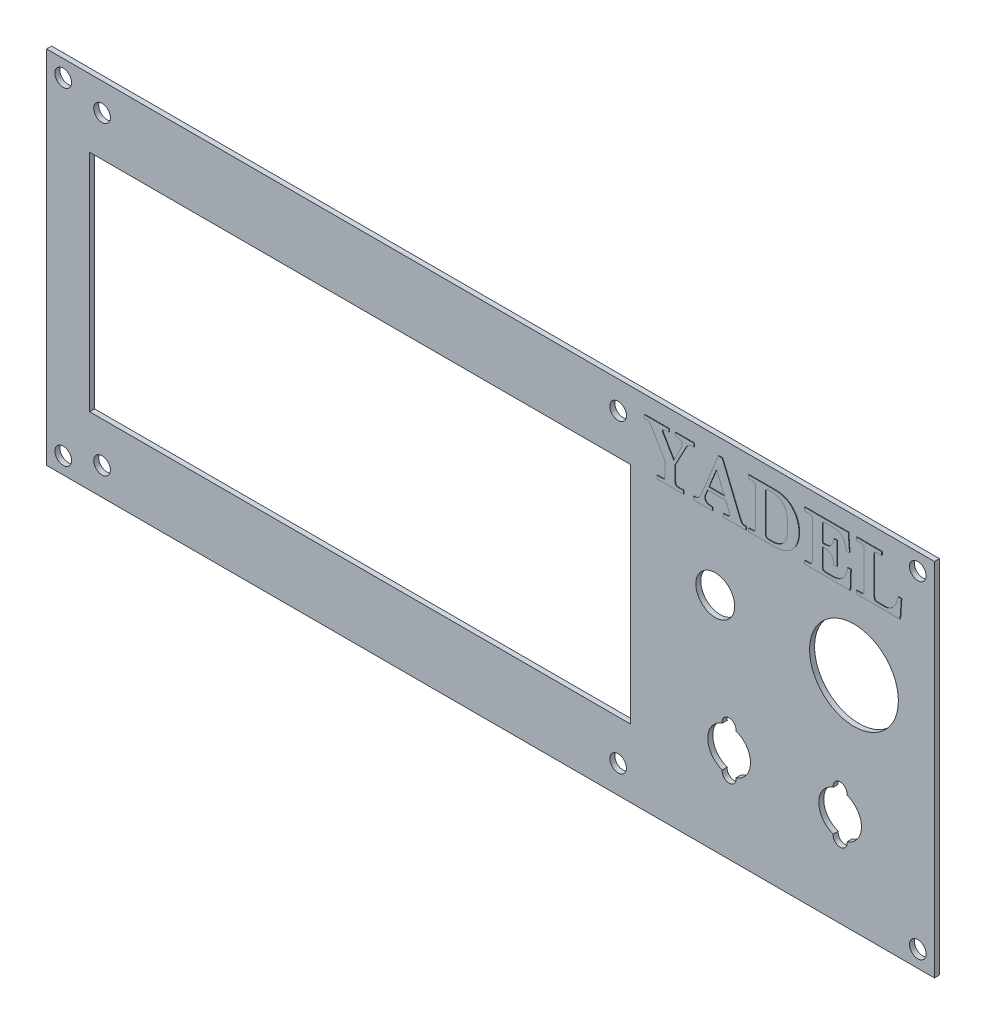
SolidWorks part; units mm, degrees
ref_plane "Plan de face" through (0, 0, 0) normal (0, 0, 1) x (1, 0, 0)
ref_plane "Plan de dessus" through (0, 0, 0) normal (0, 1, 0) x (1, 0, 0)
ref_plane "Plan de droite" through (0, 0, 0) normal (1, 0, 0) x (0, 0, -1)
sketch "Esquisse1" plane through (0, 0, 0) normal (0, 0, 1) x (1, 0, 0)
  line L1 (0, 0) -> (160, 0)
  line L2 (0, 0) -> (0, 65)
  line L3 (0, 65) -> (160, 65)
  line L4 (160, 0) -> (160, 65)
  circle A0 centre (3, 62) radius 1.5
  circle A1 centre (3, 3) radius 1.5
  circle A2 centre (157, 3) radius 1.5
  circle A3 centre (157, 62) radius 1.5
  point P13 (0, 0)
  point P15 (157.8238, 0)
  dimension "D9" = 3
  dimension "D10" = 3
  dimension "D11" = 3
  dimension "D12" = 3
  dimension "D1" = 65
  dimension "D2" = 160
  dimension "D3" = 3
  dimension "D4" = 3
  dimension "D5" = 3
  dimension "D6" = 3
  dimension "D7" = 3
  dimension "D8" = 3
  dimension "D13" = 3
  dimension "D14" = 3
extrude "Boss.-Extru.1" add sketch "Esquisse1" along normal blind 0.9
sketch "Esquisse2" plane through (0, 0, 0.9) normal (0, 0, 1) x (1, 0, 0)
  line L1 (7.75, 52.75) -> (105.25, 52.75)
  line L2 (7.75, 52.75) -> (7.75, 12.25)
  line L3 (7.75, 12.25) -> (105.25, 12.25)
  line L4 (105.25, 52.75) -> (105.25, 12.25)
  line L5 (7.5, 62.5) -> (105.5, 62.5)
  line L6 (7.5, 62.5) -> (7.5, 2.5)
  line L7 (7.5, 2.5) -> (105.5, 2.5)
  line L8 (105.5, 62.5) -> (105.5, 2.5)
  line L9 (0, 65) -> (0, 0) construction
  line L10 (143, 22.1) -> (143, 11.9) construction
  line L11 (123, 11.9) -> (123, 22.1) construction
  line L12 (123, 17) -> (143, 17) construction
  line L14 (145.5, 40) -> (120.5, 40) construction
  line L16 (160, 0) -> (160, 65) construction
  line L17 (160, 65) -> (0, 65) construction
  line L18 (0, 0) -> (160, 0) construction
  circle A0 centre (10, 5) radius 1.5
  circle A1 centre (103, 5) radius 1.5
  circle A2 centre (103, 60) radius 1.5
  circle A3 centre (10, 60) radius 1.5
  circle A4 centre (123, 17) radius 3.85
  circle A5 centre (143, 17) radius 3.85
  circle A6 centre (123, 20.85) radius 1.25
  circle A7 centre (123, 13.15) radius 1.25
  circle A8 centre (143, 20.85) radius 1.25
  circle A9 centre (143, 13.15) radius 1.25
  circle A10 centre (120.5, 40) radius 3.5
  circle A11 centre (145.5, 40) radius 8
  circle A12 centre (120.5, 40) radius 10
  point P18 (0, 32.5)
  point P19 (7.5, 32.5)
  point P20 (7.75, 32.5)
  point P21 (56.5, 62.5)
  point P22 (56.5, 52.75)
  point P42 (133, 40)
  point P46 (133, 17)
  dimension "D7" = 3
  dimension "D8" = 3
  dimension "D9" = 3
  dimension "D10" = 3
  dimension "D11" = 2.5
  dimension "D12" = 2.5
  dimension "D16" = 2.5
  dimension "D18" = 7.7
  dimension "D19" = 7.7
  dimension "D20" = 2.5
  dimension "D21" = 2.5
  dimension "D22" = 2.5
  dimension "D23" = 2.5
  dimension "D24" = 20
  dimension "D25" = 7
  dimension "D26" = 16
  dimension "D1" = 97.5
  dimension "D2" = 40.5
  dimension "D3" = 93
  dimension "D4" = 93
  dimension "D5" = 55
  dimension "D6" = 55
  dimension "D13" = 2.5
  dimension "D14" = 2.5
  dimension "D15" = 2.5
  dimension "D17" = 10
  dimension "D27" = 25
  dimension "D28" = 27
  dimension "D29" = 25
  dimension "D30" = 17
extrude "Enlèv. mat.-Extru.1" cut sketch "Esquisse2" against normal blind 0.9 contours A11 | A10 | A7 A4 A6 | A9 A5 A8 | A5 A8 | A5 A8 | A5 A9 | A5 A9 | A4 A6 | A4 A6 | A4 A7 | A4 A7 | L4 L1 L2 L3 | A3 | A0 | A1 | A2
sketch "Esquisse3" plane through (0, 0, 0.9) normal (0, 0, 1) x (1, 0, 0)
  line L0 (105, 53) -> (155, 53) construction
  line L1 (160, 65) -> (0, 65) construction
  line L2 (160, 0) -> (160, 65) construction
  text T0 "<b>YADEL</b>" font "Century Schoolbook" height in points 34
  point P5 (130, 53)
  point P8 (0, 0)
  dimension "D1" = 12
  dimension "D2" = 30
  dimension "D3" = 50
extrude "Boss.-Extru.2" add sketch "Esquisse3" along normal blind 0.1
